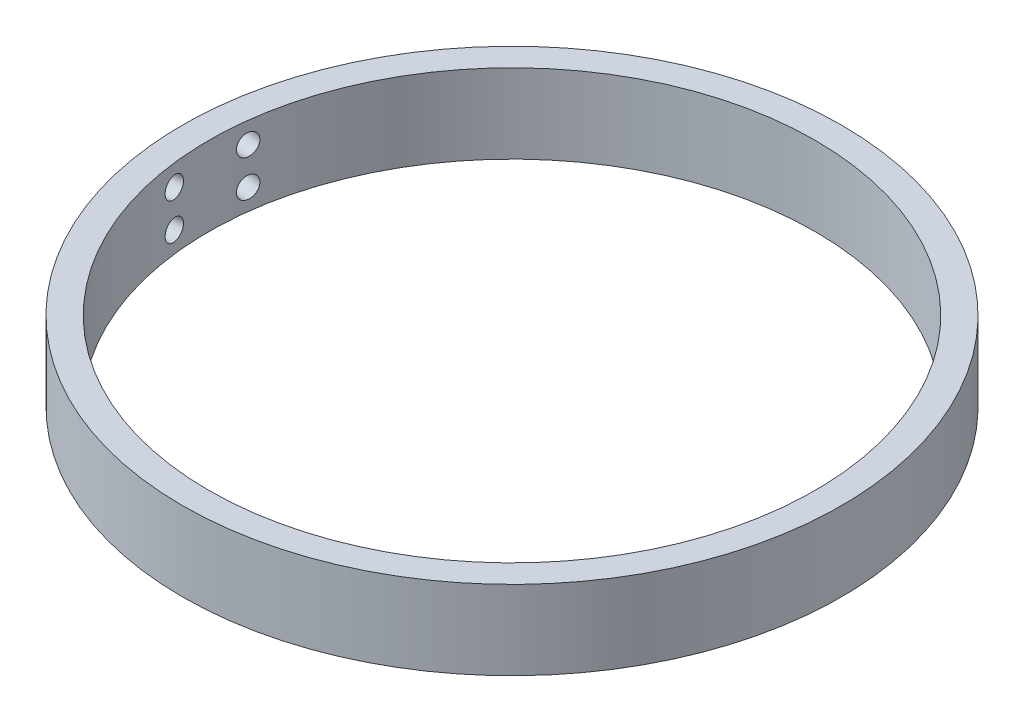
SolidWorks part; units mm, degrees
material "PVC 僵硬"
ref_plane "前视基准面" through (0, 0, 0) normal (0, 0, 1) x (1, 0, 0)
ref_plane "上视基准面" through (0, 0, 0) normal (0, 1, 0) x (1, 0, 0)
ref_plane "右视基准面" through (0, 0, 0) normal (1, 0, 0) x (0, 0, -1)
sketch "草图1" plane through (0, 0, 0) normal (0, 1, 0) x (1, 0, 0)
  circle A0 centre (0, 0) radius 57.5
  circle A1 centre (0, 0) radius 62.5
  dimension "D1" = 115
  dimension "D2" = 5
extrude "凸台-拉伸1" add sketch "草图1" along normal blind 15
sketch3d "3D草图1" plane through (0, 0, 0) normal (0, 0, 1) x (1, 0, 0)
sketch3d "3D草图2" plane through (0, 0, 0) normal (0, 0, 1) x (1, 0, 0)
sketch3d "3D草图3" plane through (0, 0, 0) normal (0, 0, 1) x (1, 0, 0)
  dimension "D1" = 7
sketch3d "3D草图4" plane through (0, 0, 0) normal (0, 0, 1) x (1, 0, 0)
  dimension "D1" = 7
sketch3d "3D草图5" plane through (0, 0, 0) normal (0, 0, 1) x (1, 0, 0)
  dimension "D1" = 90
sketch "草图3" plane through (0, 0, 0) normal (0.9925, 0, -0.1219) x (-0.1219, 0, -0.9925)
  line L0 (62.5, 15) -> (-62.5, 15) construction
  line L1 (-62.5, 0) -> (62.5, 0) construction
  line L2 (0, 50) -> (0, -50) construction
  circle A0 centre (0, 11) radius 2
  circle A1 centre (0, 4) radius 2
  dimension "D1" = 4
  dimension "D2" = 4
  dimension "D3" = 4
  dimension "D4" = 4
extrude "切除-拉伸1" cut sketch "草图3" against normal blind 71
sketch3d "3D草图6" plane through (0, 0, 0) normal (0, 0, 1) x (1, 0, 0)
  dimension "D1" = 90
sketch "草图4" plane through (0, 0, 0) normal (0.9925, 0, 0.1219) x (0.1219, 0, -0.9925)
  line L0 (57.5, 15) -> (-57.5, 15) construction
  line L1 (-62.5, 0) -> (62.5, 0) construction
  line L2 (0, 50) -> (0, -50) construction
  circle A0 centre (0, 11) radius 2
  circle A1 centre (0, 4) radius 2
  dimension "D1" = 4
  dimension "D2" = 4
  dimension "D3" = 4
  dimension "D4" = 4
extrude "切除-拉伸2" cut sketch "草图4" against normal blind 71
